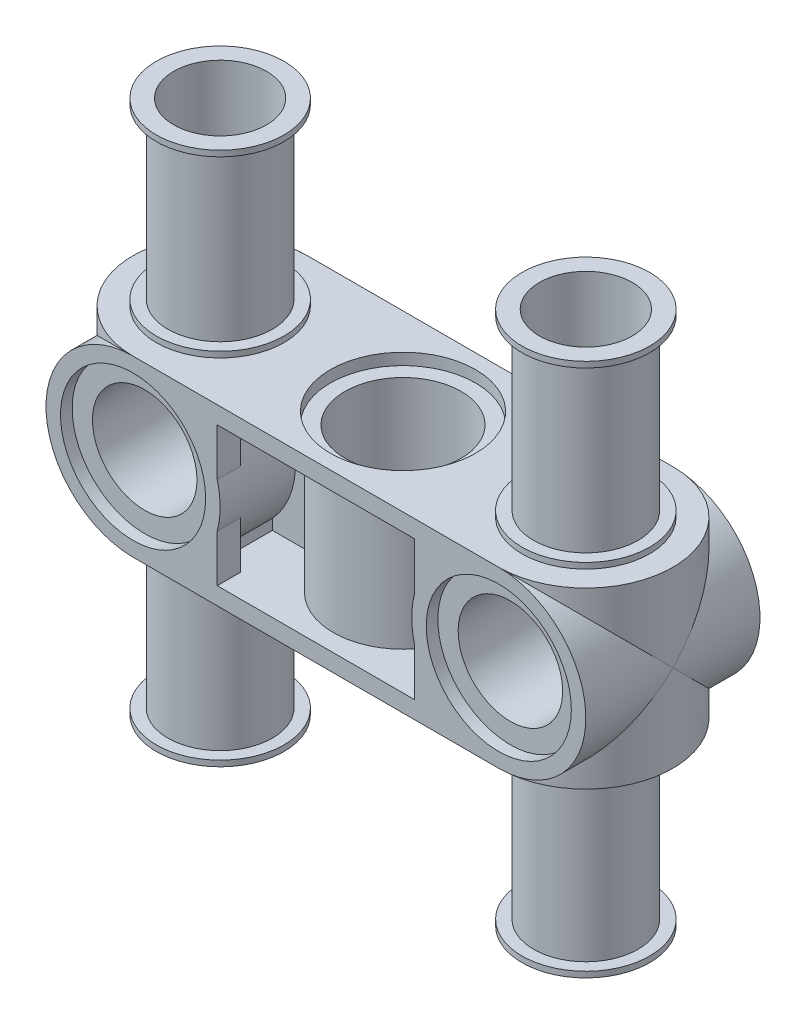
SolidWorks part; units mm, degrees
material "ABS PC"
ref_plane "Front Plane" through (0, 0, 0) normal (0, 0, 1) x (1, 0, 0)
ref_plane "Top Plane" through (0, 0, 0) normal (0, 1, 0) x (1, 0, 0)
ref_plane "Right Plane" through (0, 0, 0) normal (1, 0, 0) x (0, 0, -1)
sketch "Sketch1" plane through (0, 0, 0) normal (0, 1, 0) x (1, 0, 0)
  line L0 (-19.2625, 0) -> (26.4221, 0) construction
  line L1 (-8.001, 3.81) -> (8.001, 3.81)
  line L2 (0, 0) -> (0, 11.754) construction
  line L3 (8.001, -3.81) -> (-8.001, -3.81)
  circle A0 centre (-8.001, 0) radius 2.54 construction
  circle A1 centre (0, 0) radius 2.54 construction
  circle A2 centre (8.001, 0) radius 2.54 construction
  arc A3 (8.001, -3.81) -> (8.001, 3.81) centre (8.001, 0) ccw
  arc A4 (-8.001, 3.81) -> (-8.001, -3.81) centre (-8.001, 0) ccw
  dimension "D3" = 5.08
  dimension "D4" = 7.62
  dimension "D1" = 8.001
  dimension "D2" = 8.001
extrude "Extrude1" add sketch "Sketch1" along normal blind 3.81
sketch "Sketch2" plane through (0, 0, 0) normal (0, -1, 0) x (1, 0, 0)
  circle A0 centre (0, 0) radius 2.794
  dimension "D1" = 5.588
extrude "Cut-Extrude1" cut sketch "Sketch2" against normal blind 0.254
sketch "Sketch3" plane through (0, 0, 0) normal (0, -1, 0) x (1, 0, 0)
  circle A0 centre (8.001, 0) radius 2.794
  circle A1 centre (-8.001, 0) radius 2.794
  arc A3 (8.001, -3.81) -> (8.001, 3.81) centre (8.001, 0) ccw construction
  dimension "D1" = 5.588
  dimension "D2" = 8.001
extrude "Extrude2" add sketch "Sketch3" along normal blind 0.254
sketch "Sketch5" plane through (0, -0.254, 0) normal (0, -1, 0) x (1, 0, 0)
  circle A0 centre (8.001, 0) radius 2.794 construction
  circle A1 centre (8.001, 0) radius 2.286
  circle A2 centre (-8.001, 0) radius 2.794 construction
  circle A3 centre (8.001, 0) radius 2.032
  circle A4 centre (-8.001, 0) radius 2.286
  circle A8 centre (-8.001, 0) radius 2.032
  dimension "D2" = 4.572
  dimension "D1" = 4.064
extrude "Extrude4" add sketch "Sketch5" along normal blind 7.366
sketch "Sketch6" plane through (0, -7.62, 0) normal (0, -1, 0) x (1, 0, 0)
  circle A1 centre (-8.001, 0) radius 2.032 construction
  circle A3 centre (8.001, 0) radius 2.032 construction
  circle A4 centre (-8.001, 0) radius 2.794 construction
  circle A5 centre (8.001, 0) radius 2.794 construction
  circle A6 centre (-8.001, 0) radius 2.794
  circle A7 centre (8.001, 0) radius 2.794
  circle A8 centre (8.001, 0) radius 2.032
  circle A9 centre (-8.001, 0) radius 2.032
extrude "Extrude5" add sketch "Sketch6" along normal blind 0.254
sketch "Sketch7" plane through (0, 0, -3.81) normal (0, 0, -1) x (-1, 0, 0)
  line L0 (-8.001, 3.81) -> (8.001, 3.81) construction
  line L2 (-8.001, 0) -> (8.001, 0) construction
  line L3 (-8.001, 0) -> (8.001, 0)
  line L4 (-8.001, 3.81) -> (8.001, 3.81)
  line L5 (-8.001, 3.81) -> (-11.811, 3.81)
  line L6 (8.001, 3.81) -> (11.811, 3.81)
  arc A0 (-11.811, 3.81) -> (-8.001, 0) centre (-8.001, 3.81) ccw
  arc A1 (8.001, 0) -> (11.811, 3.81) centre (8.001, 3.81) ccw
extrude "Extrude6" add sketch "Sketch7" against normal blind 7.112
sketch "Sketch8" plane through (0, 3.81, 0) normal (0, 1, 0) x (1, 0, 0)
  circle A0 centre (-8.001, 0) radius 2.54 construction
  circle A1 centre (0, 0) radius 2.54 construction
  circle A2 centre (8.001, 0) radius 2.54 construction
  circle A3 centre (-8.001, 0) radius 2.54 construction
  circle A4 centre (0, 0) radius 2.54
  circle A5 centre (8.001, 0) radius 2.54 construction
extrude "Cut-Extrude2" cut sketch "Sketch8" against normal blind 3.556
sketch "Sketch9" plane through (0, 0, 3.81) normal (0, 0, 1) x (1, 0, 0)
  line L0 (11.811, 3.81) -> (-11.811, 3.81) construction
  circle A0 centre (8.001, 3.81) radius 2.286
  circle A1 centre (-8.001, 3.81) radius 2.286
  dimension "D1" = 4.572
  dimension "D2" = 8.001
  dimension "D3" = 8.001
extrude "Cut-Extrude3" cut sketch "Sketch9" against normal through all
sketch "Sketch10" plane through (0, 0, 3.81) normal (0, 0, 1) x (1, 0, 0)
  circle A0 centre (8.001, 3.81) radius 3.175
  circle A1 centre (-8.001, 3.81) radius 3.175
  dimension "D1" = 6.35
extrude "Cut-Extrude4" cut sketch "Sketch10" against normal blind 0.508
mirror "Mirror2" about plane through (0, 0, 0) normal (0, 0, 1) of "Cut-Extrude4"
sketch "Sketch11" plane through (0, 3.81, 0) normal (0, 1, 0) x (1, 0, 0)
  line L0 (-5.207, -0.508) -> (-5.207, -2.794)
  line L1 (5.207, 0.508) -> (5.207, 2.794)
  line L2 (5.207, -2.794) -> (5.207, -0.508)
  line L23 (4.826, 3.81) -> (-4.826, 3.81) construction
  line L24 (-5.809, 0) -> (6.5071, 0) construction
  line L25 (-5.207, 0.508) -> (-3.0054, 0.508)
  line L26 (-5.809, 0.508) -> (6.5071, 0.508) construction
  line L27 (-5.207, -0.508) -> (-3.0054, -0.508)
  line L28 (-5.809, -0.508) -> (6.5071, -0.508) construction
  line L29 (-4.826, -3.81) -> (4.826, -3.81) construction
  line L30 (-4.318, -3.81) -> (4.318, -3.81)
  line L31 (3.0054, -0.508) -> (5.207, -0.508)
  line L32 (-4.318, -2.794) -> (-4.318, -3.302)
  line L33 (-4.318, -3.302) -> (4.318, -3.302)
  line L34 (4.318, -3.302) -> (4.318, -2.794)
  line L35 (4.318, -2.794) -> (5.207, -2.794)
  line L36 (5.207, -2.794) -> (5.207, 2.794)
  line L37 (4.318, 3.302) -> (-4.318, 3.302)
  line L38 (4.318, 3.81) -> (-4.318, 3.81)
  line L39 (-4.318, 3.302) -> (-4.318, 2.794)
  line L40 (-5.207, 2.794) -> (-5.207, -2.794)
  line L41 (-5.207, -2.794) -> (-4.318, -2.794)
  line L42 (-4.318, -2.794) -> (-4.318, -3.81)
  line L43 (3.0054, 0.508) -> (5.207, 0.508)
  line L44 (4.318, -3.81) -> (4.318, -2.794)
  line L45 (4.318, -2.794) -> (5.207, -2.794)
  line L47 (-4.318, 3.81) -> (-4.318, 2.794)
  line L49 (-4.318, 2.794) -> (-5.207, 2.794)
  line L50 (-5.207, 2.794) -> (-5.207, 0.508)
  line L51 (-5.207, -2.794) -> (-4.318, -2.794)
  line L65 (-4.318, 2.794) -> (-5.207, 2.794)
  line L70 (5.207, 2.794) -> (4.318, 2.794)
  line L71 (5.207, 2.794) -> (4.318, 2.794)
  line L72 (4.318, 2.794) -> (4.318, 3.302)
  line L73 (4.318, 2.794) -> (4.318, 3.81)
  circle A5 centre (0, 0) radius 3.048
  arc A6 (-3.0054, -0.508) -> (3.0054, -0.508) centre (0, 0) ccw
  arc A8 (3.0054, 0.508) -> (-3.0054, 0.508) centre (0, 0) ccw
  dimension "D1" = 0.508
  dimension "D2" = 0.508
  dimension "D3" = 0.508
  dimension "D4" = 0.508
extrude "Cut-Extrude6" cut sketch "Sketch11" against normal blind 3.048
sketch "Sketch13" plane through (0, 0.254, 0) normal (0, 1, 0) x (1, 0, 0)
  circle A1 centre (0, 0) radius 2.54
  circle A2 centre (0, 0) radius 2.54
  dimension "D1" = 0
extrude "Cut-Extrude7" cut sketch "Sketch13" against normal through all
sketch "Sketch14" plane through (0, 0, 0) normal (0, -1, 0) x (1, 0, 0)
  circle A0 centre (0, 0) radius 3.175
  dimension "D1" = 6.35
extrude "Cut-Extrude8" cut sketch "Sketch14" against normal blind 0.508
sketch "Sketch17" plane through (0, 0, 3.81) normal (0, 0, 1) x (1, 0, 0)
  line L0 (-4.191, 3.81) -> (-4.826, 3.81)
  line L1 (-11.811, 3.81) -> (-11.176, 3.81)
  arc A0 (-11.811, 3.81) -> (-4.191, 3.81) centre (-8.001, 3.81) ccw
  arc A1 (-9.9018, 1.2668) -> (-4.826, 3.81) centre (-8.001, 3.81) ccw construction
  arc A2 (-11.176, 3.81) -> (-4.826, 3.81) centre (-8.001, 3.81) ccw
  dimension "D1" = 3.81
extrude "Extrude8" add sketch "Sketch17" against normal blind 7.112
mirror "Mirror3" about plane through (0, 0, 0) normal (1, 0, 0) of "Extrude8"
mirror "Mirror1" of bodies 118 111
